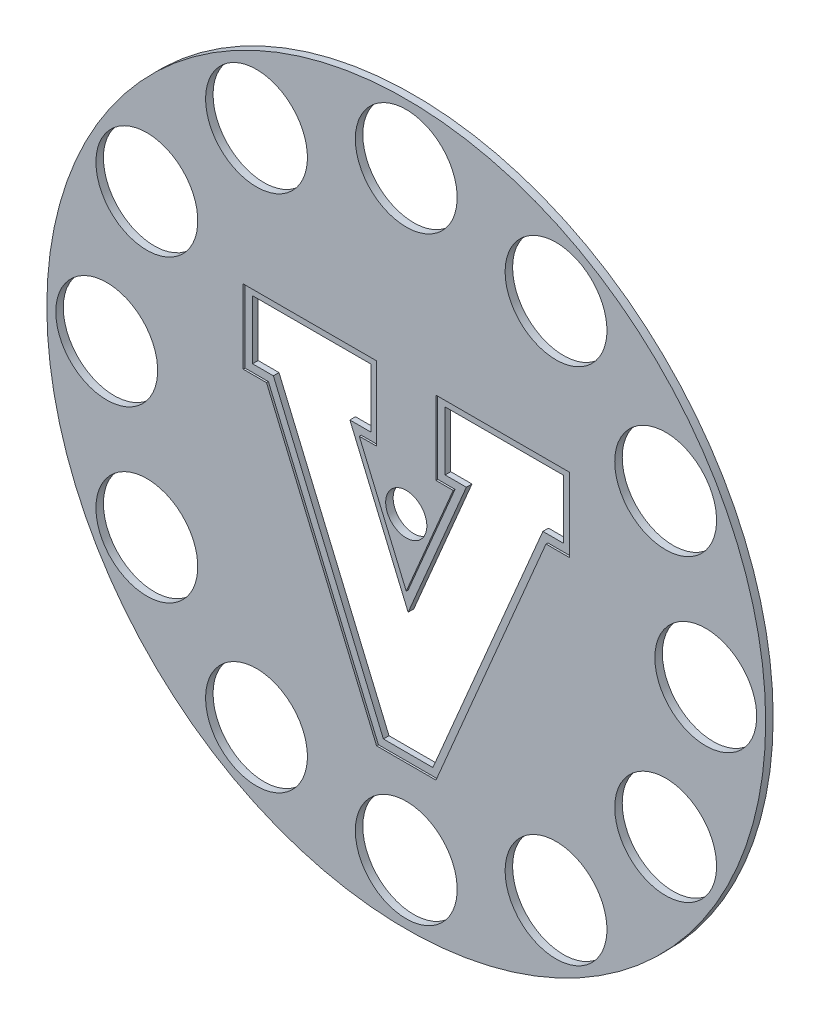
SolidWorks part; units mm, degrees
material "Mahogany"
ref_plane "Front Plane" through (0, 0, 0) normal (0, 0, 1) x (1, 0, 0)
ref_plane "Top Plane" through (0, 0, 0) normal (0, 1, 0) x (1, 0, 0)
ref_plane "Right Plane" through (0, 0, 0) normal (1, 0, 0) x (0, 0, -1)
sketch "Sketch1" plane through (0, 0, 0) normal (0, 0, 1) x (1, 0, 0)
  line L0 (0, 508) -> (0, 0) construction
  line L1 (-9.0217, 784.0457) -> (1590.9783, 784.0457) construction
  line L2 (-263.8171, 187.3155) -> (-62.7583, 187.3155)
  line L3 (-62.7583, 187.3155) -> (-62.7583, 87.3671)
  line L4 (-62.7583, 87.3671) -> (-98.7862, 87.3671)
  line L5 (-98.7862, 87.3671) -> (0, -145.652)
  line L7 (41.9693, -352.7389) -> (-41.9693, -352.7389)
  line L8 (-41.9693, -352.7389) -> (-228.5479, 87.3671)
  line L9 (-228.5479, 87.3671) -> (-263.8171, 87.3671)
  line L10 (-263.8171, 87.3671) -> (-263.8171, 187.3155)
  line L11 (228.5479, 87.3671) -> (263.8171, 87.3671)
  line L12 (41.9693, -352.7389) -> (228.5479, 87.3671)
  line L13 (98.7862, 87.3671) -> (0, -145.652)
  line L14 (62.7583, 87.3671) -> (98.7862, 87.3671)
  line L15 (62.7583, 187.3155) -> (62.7583, 87.3671)
  line L16 (263.8171, 187.3155) -> (62.7583, 187.3155)
  line L17 (263.8171, 87.3671) -> (263.8171, 187.3155)
  circle A0 centre (0, 0) radius 609.6
  circle A2 centre (0, 508) radius 86.36
  circle A3 centre (254, 439.9409) radius 86.36
  circle A4 centre (439.9409, 254) radius 86.36
  circle A5 centre (508, 0) radius 86.36
  circle A6 centre (439.9409, -254) radius 86.36
  circle A7 centre (254, -439.9409) radius 86.36
  circle A8 centre (0, -508) radius 86.36
  circle A9 centre (-254, -439.9409) radius 86.36
  circle A10 centre (-439.9409, -254) radius 86.36
  circle A11 centre (-508, 0) radius 86.36
  circle A12 centre (-439.9409, 254) radius 86.36
  circle A13 centre (-254, 439.9409) radius 86.36
  circle A14 centre (0, 0) radius 34.925
  point P29 (0, 0)
  dimension "D1" = 1219.2
  dimension "D2" = 172.72
  dimension "D5" = 69.85
  dimension "D3" = 508
  dimension "D4" = 12
extrude "Boss-Extrude1" add sketch "Sketch1" along normal blind 12.7
sketch "Sketch2" plane through (0, 0, 12.7) normal (0, 0, 1) x (1, 0, 0)
  line L126 (11.6927, -140.695) -> (-79.608, 74.6671)
  line L127 (-236.958, 74.6671) -> (-53.6619, -357.6959)
  line L128 (-276.5171, 74.6671) -> (-236.958, 74.6671)
  line L129 (-79.608, 74.6671) -> (-50.0583, 74.6671)
  line L130 (-50.0583, 74.6671) -> (-50.0583, 200.0155)
  line L131 (-276.5171, 200.0155) -> (-276.5171, 74.6671)
  line L132 (-50.0583, 200.0155) -> (-276.5171, 200.0155)
  line L133 (0, -113.1141) -> (-79.608, 74.6671)
  line L135 (-276.5171, 74.6671) -> (-236.958, 74.6671)
  line L136 (-79.608, 74.6671) -> (-50.0583, 74.6671)
  line L137 (-50.0583, 74.6671) -> (-50.0583, 200.0155)
  line L138 (-276.5171, 200.0155) -> (-276.5171, 74.6671)
  line L139 (-50.0583, 200.0155) -> (-276.5171, 200.0155)
  line L198 (0, -113.1141) -> (-87.0935, 92.3241)
  line L199 (-240.2406, 82.4102) -> (-50.3794, -365.4389)
  line L200 (-50.3794, -365.4389) -> (50.3794, -365.4389)
  line L201 (50.3794, -365.4389) -> (236.958, 74.6671)
  line L202 (236.958, 74.6671) -> (276.5171, 74.6671)
  line L203 (276.5171, 74.6671) -> (276.5171, 200.0155)
  line L204 (276.5171, 200.0155) -> (50.0583, 200.0155)
  line L205 (50.0583, 200.0155) -> (50.0583, 74.6671)
  line L206 (50.0583, 74.6671) -> (79.608, 74.6671)
  line L207 (79.608, 74.6671) -> (0, -113.1141)
  line L208 (0, -113.1141) -> (-79.608, 74.6671)
  line L209 (-236.958, 74.6671) -> (-50.3794, -365.4389)
  line L210 (-50.3794, -365.4389) -> (50.3794, -365.4389)
  line L211 (50.3794, -365.4389) -> (236.958, 74.6671)
  line L212 (236.958, 74.6671) -> (276.5171, 74.6671)
  line L213 (276.5171, 74.6671) -> (276.5171, 200.0155)
  line L214 (276.5171, 200.0155) -> (50.0583, 200.0155)
  line L215 (50.0583, 200.0155) -> (50.0583, 74.6671)
  line L216 (50.0583, 74.6671) -> (79.608, 74.6671)
  line L217 (79.608, 74.6671) -> (0, -113.1141)
  line M14 (-228.5479, 87.3671) -> (-263.8171, 87.3671)
  line M15 (-263.8171, 87.3671) -> (-263.8171, 187.3155)
  line M16 (-263.8171, 187.3155) -> (-62.7583, 187.3155)
  line M17 (-62.7583, 187.3155) -> (-62.7583, 87.3671)
  line M18 (-62.7583, 87.3671) -> (-98.7862, 87.3671)
  line M19 (-98.7862, 87.3671) -> (0, -145.652)
  line M20 (0, -145.652) -> (98.7862, 87.3671)
  line M21 (98.7862, 87.3671) -> (62.7583, 87.3671)
  line M22 (62.7583, 87.3671) -> (62.7583, 187.3155)
  line M23 (62.7583, 187.3155) -> (263.8171, 187.3155)
  line M24 (263.8171, 187.3155) -> (263.8171, 87.3671)
  line M25 (263.8171, 87.3671) -> (228.5479, 87.3671)
  line M26 (228.5479, 87.3671) -> (41.9693, -352.7389)
  line M27 (41.9693, -352.7389) -> (-41.9693, -352.7389)
  line M28 (-41.9693, -352.7389) -> (-228.5479, 87.3671)
  dimension "D1" = 12.7
  dimension "D2" = 12.7
extrude "Cut-Extrude1" cut sketch "Sketch2" against normal blind 3.175 and the other way through all contours L216 L217 L133 L136 L137 L139 L138 L135 L209 L210 L211 L212 L213 L214 L215 M28 M14 M15 M16 M17 M18 M19 M20 M21 M22 M23 M24 M25 M26 M27
sketch "Sketch3" plane through (0, 0, 12.7) normal (0, 0, 1) x (1, 0, 0)
  line B0 (50.0583, 109.1195) -> (79.608, 109.1195)
  line B1 (79.608, 109.1195) -> (0, -78.6617)
  line B2 (0, -78.6617) -> (-79.608, 109.1195)
  line B3 (-79.608, 109.1195) -> (-50.0583, 109.1195)
  line B4 (-50.0583, 109.1195) -> (-50.0583, 234.4679)
  line B5 (-50.0583, 234.4679) -> (-276.5171, 234.4679)
  line B6 (-276.5171, 234.4679) -> (-276.5171, 109.1195)
  line B7 (-276.5171, 109.1195) -> (-236.958, 109.1195)
  line B8 (-236.958, 109.1195) -> (-50.3794, -330.9865)
  line B9 (-50.3794, -330.9865) -> (50.3794, -330.9865)
  line B10 (50.3794, -330.9865) -> (236.958, 109.1195)
  line B11 (236.958, 109.1195) -> (276.5171, 109.1195)
  line B12 (276.5171, 109.1195) -> (276.5171, 234.4679)
  line B13 (276.5171, 234.4679) -> (50.0583, 234.4679)
  line B14 (50.0583, 234.4679) -> (50.0583, 109.1195)
  line B15 (41.9693, -318.2865) -> (-41.9693, -318.2865)
  line B16 (228.5479, 121.8195) -> (41.9693, -318.2865)
  line B17 (263.8171, 121.8195) -> (228.5479, 121.8195)
  line B18 (263.8171, 221.7679) -> (263.8171, 121.8195)
  line B19 (62.7583, 221.7679) -> (263.8171, 221.7679)
  line B20 (62.7583, 121.8195) -> (62.7583, 221.7679)
  line B21 (98.7862, 121.8195) -> (62.7583, 121.8195)
  line B22 (0, -111.1996) -> (98.7862, 121.8195)
  line B23 (-98.7862, 121.8195) -> (0, -111.1996)
  line B24 (-62.7583, 121.8195) -> (-98.7862, 121.8195)
  line B25 (-62.7583, 221.7679) -> (-62.7583, 121.8195)
  line B26 (-263.8171, 221.7679) -> (-62.7583, 221.7679)
  line B27 (-263.8171, 121.8195) -> (-263.8171, 221.7679)
  line B28 (-228.5479, 121.8195) -> (-263.8171, 121.8195)
  line B29 (-41.9693, -318.2865) -> (-228.5479, 121.8195)
sketch_block_instance "Block1-1"
sketch_block "Block1"
